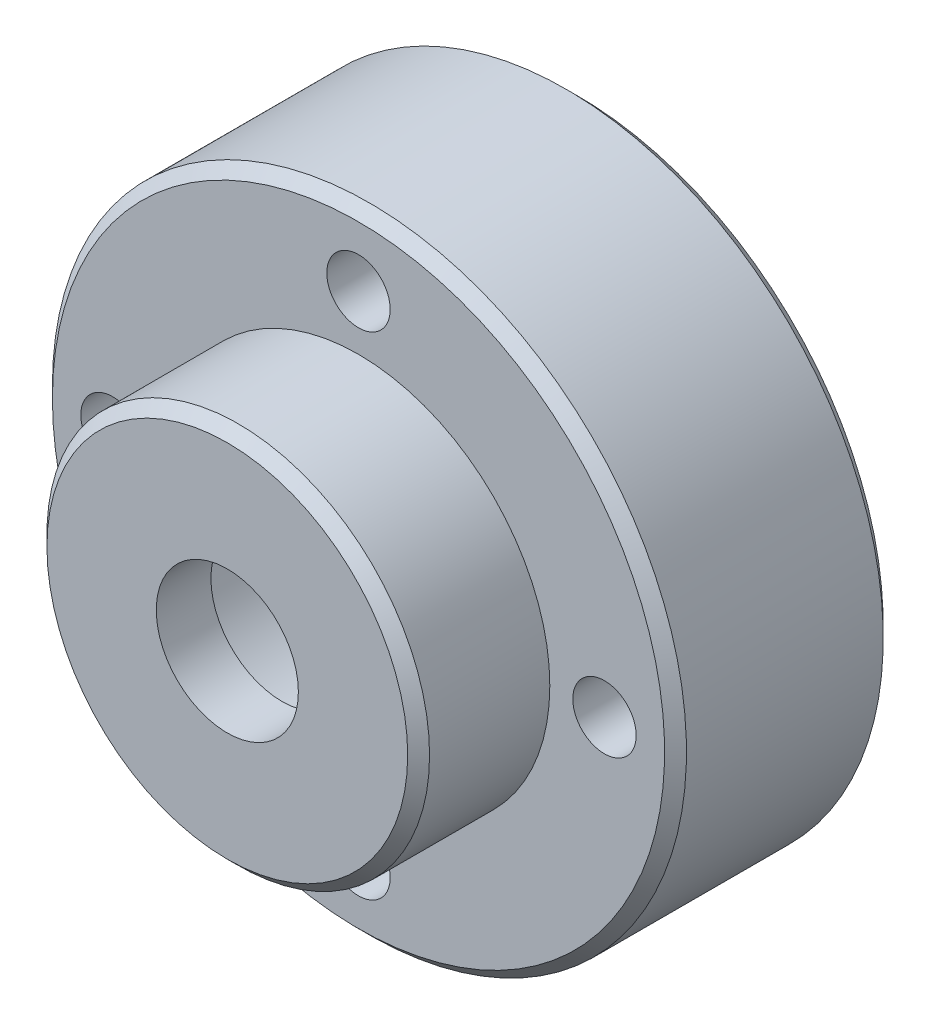
SolidWorks part; units mm, degrees
material "SKD11淬火HRC56-60"
ref_plane "前基準面" through (0, 0, 0) normal (0, 0, 1) x (1, 0, 0)
ref_plane "上基準面" through (0, 0, 0) normal (0, 1, 0) x (1, 0, 0)
ref_plane "右基準面" through (0, 0, 0) normal (1, 0, 0) x (0, 0, -1)
sketch "草图1" plane through (0, 0, 0) normal (0, 0, 1) x (1, 0, 0)
  circle A0 centre (0, 0) radius 17.5
  dimension "D1" = 35
extrude "凸台-拉伸1" add sketch "草图1" against normal blind 12
sketch "草图2" plane through (0, 0, -12) normal (0, 0, -1) x (-1, 0, 0)
  circle A0 centre (0, 0) radius 29
  dimension "D1" = 58
extrude "凸台-拉伸2" add sketch "草图2" along normal blind 20
sketch "草图3" plane through (0, 0, 0) normal (0, 0, 1) x (1, 0, 0)
  circle A0 centre (0, 0) radius 6.5
  dimension "D1" = 13
extrude "切除-拉伸1" cut sketch "草图3" against normal through all
sketch "草图4" plane through (0, 0, -32) normal (0, 0, -1) x (-1, 0, 0)
  circle A0 centre (0, 0) radius 11.05
  dimension "D1" = 22.1
extrude "切除-拉伸2" cut sketch "草图4" against normal blind 27
chamfer "倒角1" distance 1 angle 45 3 edges at (-29, 0, -12) (17.5, 0, 0) (-29, 0, -32)
hole_wizard "M5 六角凹头螺钉的柱形沉头孔1" positions "草图6" profile "草图5" counterbore size "M5" standard "ISO" end condition through all
sketch "草图6" plane through (0, 0, -32) normal (0, 0, -1) x (-1, 0, 0)
  line L0 (0, 0) -> (45, 0) construction
  line L1 (0, 0) -> (0, 32.197) construction
  line L2 (0, 0) -> (-40.4551, 0) construction
  line L3 (0, 0) -> (0, -35.0585) construction
  circle A0 centre (0, 0) radius 22.5 construction
  point P0 (0, 22.5)
  point P1 (-22.5, 0)
  point P3 (0, -22.5)
  point P5 (22.5, 0)
  dimension "D1" = 45
sketch "草图5" plane through (0, 22.5, -32) normal (1, 0, 0) x (0, 1, 0)
  line L0 (0, 0) -> (0, 32)
  line L1 (0, 32) -> (2.9, 32)
  line L3 (2.9, 32) -> (2.9, 5)
  line L4 (2.9, 5) -> (5, 5)
  line L5 (5, 5) -> (5, 0)
  line L7 (5, 0) -> (0, 0)
  line L11 (0, -6.35) -> (0, 107.95) construction
  dimension "通孔孔直径" = 5.8
  dimension "通孔孔深度" = 32
  dimension "柱形沉头孔直径" = 10
  dimension "柱形沉头孔深度" = 5
